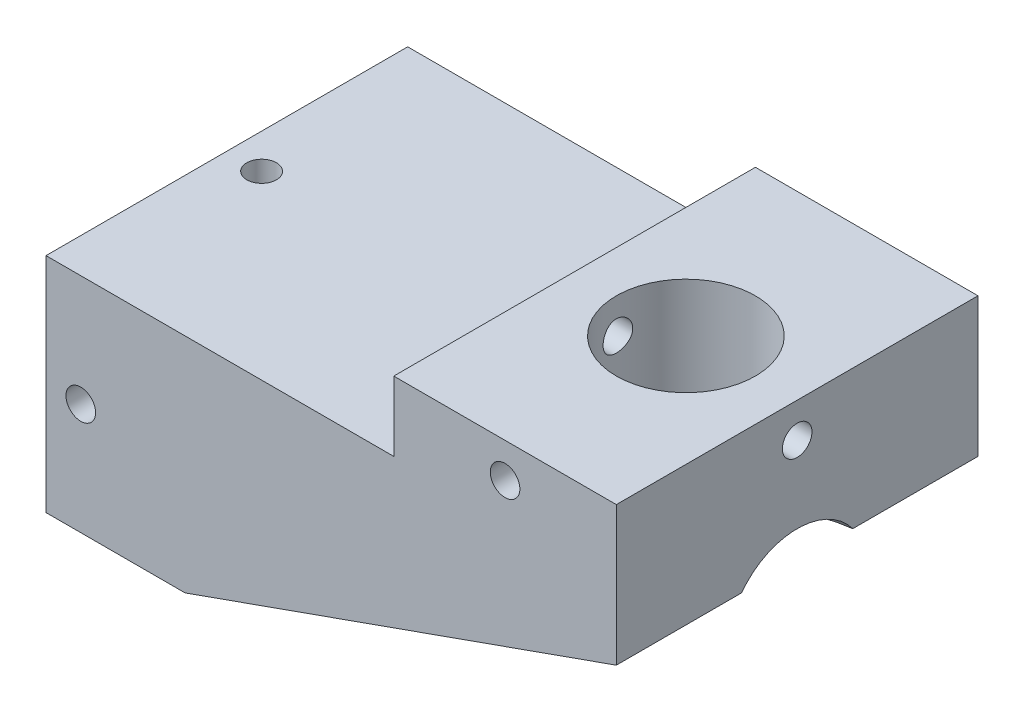
SolidWorks part; units mm, degrees
material "6061 Alloy"
ref_plane "Front Plane" through (0, 0, 0) normal (0, 0, 1) x (1, 0, 0)
ref_plane "Top Plane" through (0, 0, 0) normal (0, 1, 0) x (1, 0, 0)
ref_plane "Right Plane" through (0, 0, 0) normal (1, 0, 0) x (0, 0, -1)
sketch "Sketch1" plane through (0, 0, 0) normal (1, 0, 0) x (0, 0, -1)
  line L1 (-16.51, -10.16) -> (16.51, -10.16)
  line L2 (-16.51, -10.16) -> (-16.51, 10.16)
  line L3 (-16.51, 10.16) -> (16.51, 10.16)
  line L4 (16.51, -10.16) -> (16.51, 10.16)
  line L5 (-16.51, -10.16) -> (16.51, 10.16) construction
  line L6 (-16.51, 10.16) -> (16.51, -10.16) construction
  point P0 (0, 0)
  dimension "D1" = 33.02
  dimension "D2" = 20.32
extrude "Boss-Extrude1" add sketch "Sketch1" along normal blind 6.35
sketch "Sketch2" plane through (0, 10.16, 0) normal (0, 1, 0) x (1, 0, 0)
  line L1 (52.07, -16.51) -> (31.75, -16.51)
  line L2 (52.07, -16.51) -> (52.07, 16.51)
  line L3 (52.07, 16.51) -> (31.75, 16.51)
  line L4 (31.75, -16.51) -> (31.75, 16.51)
  line L6 (6.35, -16.51) -> (0, -16.51) construction
  line L7 (6.35, 16.51) -> (6.35, -16.51) construction
  dimension "D1" = 33.02
  dimension "D2" = 20.32
  dimension "D3" = 25.4
extrude "Boss-Extrude2" add sketch "Sketch2" along normal blind 6.35 separate body
hole_wizard "#6-32 Tapped Hole1" positions "3DSketch1" profile "Sketch5" tap size "#6-32" standard "ANSI Inch"
sketch3d "3DSketch1"
  line L0 (3.175, 10.16, -16.51) -> (3.175, -10.16, -16.51) construction
  line L1 (6.35, 10.16, -16.51) -> (0, 10.16, -16.51) construction
  line L2 (6.35, -10.16, -16.51) -> (0, -10.16, -16.51) construction
  line L8 (31.75, 13.335, -16.51) -> (52.07, 13.335, -16.51) construction
  line L9 (31.75, 16.51, -16.51) -> (31.75, 10.16, -16.51) construction
  line L10 (52.07, 10.16, -16.51) -> (52.07, 16.51, -16.51) construction
  line L13 (31.75, 13.335, -16.51) -> (31.75, 13.335, 16.51) construction
  line L14 (31.75, 16.51, 16.51) -> (31.75, 10.16, 16.51) construction
  line L16 (3.175, 10.16, -16.51) -> (3.175, 10.16, 16.51) construction
  line L17 (6.35, 10.16, 16.51) -> (0, 10.16, 16.51) construction
  line L18 (6.35, 10.16, 16.51) -> (0, 10.16, 16.51) construction
  line L19 (6.35, 10.16, -16.51) -> (0, 10.16, -16.51) construction
  point P40 (3.175, 0, -16.51)
  point P42 (3.175, 10.16, 0)
  point P44 (31.75, 13.335, 0)
  point P46 (41.91, 13.335, -16.51)
  point P57 (41.91, 13.335, 16.51)
  point P59 (52.07, 13.335, 0)
  point P61 (3.175, 0, 16.51)
  point P63 (3.175, -10.16, 0)
sketch "Sketch5" plane through (3.175, 0, -16.51) normal (1, 0, 0) x (0, 1, 0)
  line L0 (0, 0) -> (0, 9.4487)
  line L1 (0, 9.4487) -> (1.3525, 8.636)
  line L2 (1.3525, 8.636) -> (1.3525, 0)
  line L5 (1.3525, 0) -> (0, 0)
  line L10 (0, 9.4487) -> (-1.3526, 8.636) construction
  line L11 (0, -6.35) -> (0, 107.95) construction
  dimension "Tap Drill Dia." = 2.7051
  dimension "Tap Drill Depth" = 8.636
  dimension "Drill Angle" = 118
sketch "Sketch4" plane through (0, 0, -16.51) normal (0, 0, 1) x (1, 0, 0)
  line L0 (52.07, 10.16) -> (52.07, 3.81)
  line L1 (52.07, 3.81) -> (12.7, -10.16)
  line L2 (12.7, -10.16) -> (6.35, -10.16)
  line L3 (52.07, 10.16) -> (6.35, 10.16)
  line L4 (6.35, 10.16) -> (6.35, -10.16)
  dimension "D1" = 6.35
extrude "Boss-Extrude3" add sketch "Sketch4" along normal through all
sketch "Sketch6" plane through (0, 16.51, 0) normal (0, 1, 0) x (1, 0, 0)
  line L0 (41.91, 16.51) -> (41.91, -16.51) construction
  line L1 (52.07, 16.51) -> (31.75, 16.51) construction
  line L2 (31.75, -16.51) -> (52.07, -16.51) construction
  circle A0 centre (41.91, 0) radius 6.35
  dimension "D1" = 12.7
extrude "Cut-Extrude1" cut sketch "Sketch6" against normal through all
sketch "Sketch7" plane through (0, 0, 0) normal (-1, 0, 0) x (0, 0, 1)
  line L0 (-16.51, 0) -> (16.51, 0) construction
  line L1 (-16.51, -10.16) -> (-16.51, 10.16) construction
  line L2 (16.51, 10.16) -> (16.51, -10.16) construction
  circle A0 centre (0, 0) radius 6.35
  dimension "D1" = 12.7
extrude "Cut-Extrude2" cut sketch "Sketch7" against normal through all
